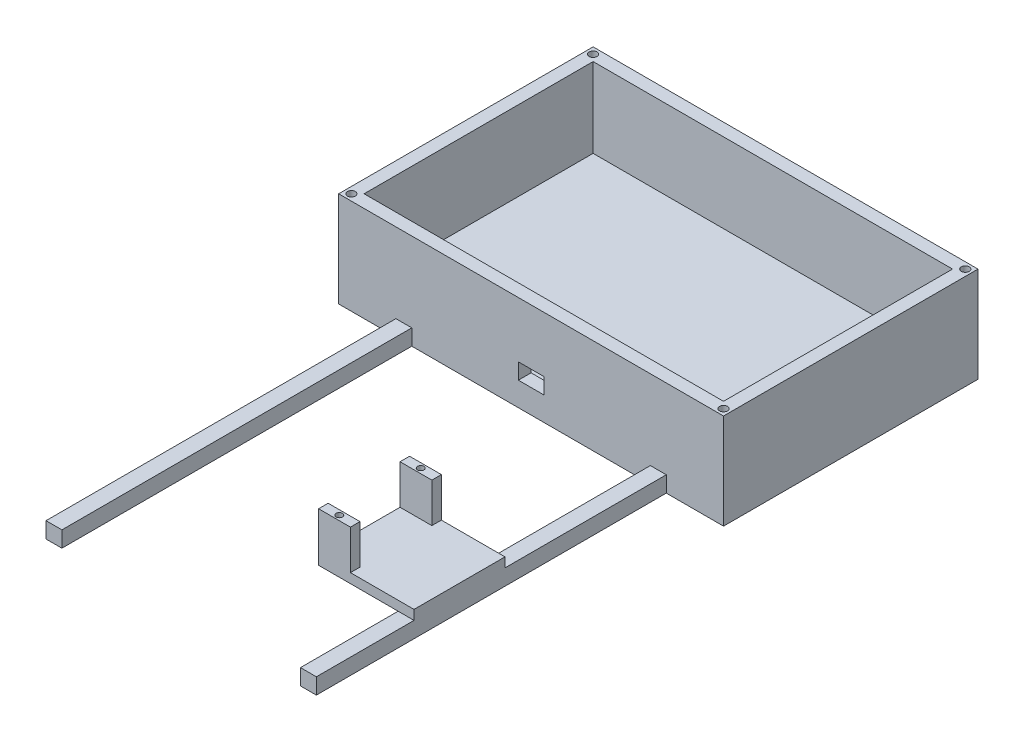
SolidWorks part; units mm, degrees
ref_plane "Front Plane" through (0, 0, 0) normal (0, 0, 1) x (1, 0, 0)
ref_plane "Top Plane" through (0, 0, 0) normal (0, 1, 0) x (1, 0, 0)
ref_plane "Right Plane" through (0, 0, 0) normal (1, 0, 0) x (0, 0, -1)
sketch "Sketch1" plane through (0, 0, 0) normal (0, 1, 0) x (1, 0, 0)
  line L5 (-55, 0) -> (55, 0) construction
  line L6 (-42.5, -81) -> (-42.5, 29)
  line L7 (-42.5, -81) -> (-37.5, -81)
  line L8 (0, -55) -> (0, 55) construction
  line L9 (42.5, -81) -> (37.5, -81)
  line L11 (-37.5, -81) -> (-37.5, 29)
  line L12 (37.5, -81) -> (37.5, 29)
  line L13 (37.5, 29) -> (-37.5, 29)
  line L14 (42.5, -81) -> (42.5, 29)
  line L15 (-42.5, 29) -> (-60.5, 29)
  line L16 (42.5, 29) -> (60.5, 29)
  line L17 (-60.5, 29) -> (-60.5, 109)
  line L18 (-60.5, 109) -> (60.5, 109)
  line L19 (60.5, 109) -> (60.5, 29)
  point P0 (0, 0)
  dimension "D1" = 110
  dimension "D2" = 18
  dimension "D3" = 29
  dimension "D4" = 5
  dimension "D5" = 110
  dimension "D6" = 80
  dimension "D7" = 75
  dimension "D8" = 18
extrude "Boss-Extrude1" add sketch "Sketch1" along normal blind 5
sketch "Sketch2" plane through (0, 5, 0) normal (0, 1, 0) x (1, 0, 0)
  line L0 (-37.5, 29) -> (-60.5, 29) construction
  line L2 (56.5, 33) -> (56.5, 105)
  line L3 (-60.5, 29) -> (60.5, 29)
  line L5 (-60.5, 109) -> (60.5, 109)
  line L7 (-56.5, 105) -> (56.5, 105)
  line L8 (-56.5, 33) -> (-56.5, 105)
  line L9 (-56.5, 33) -> (56.5, 33)
  line L10 (-60.5, 29) -> (-60.5, 109) construction
  line L11 (60.5, 29) -> (60.5, 109) construction
  line M10 (-37.5, 29) -> (37.5, 29)
  line M17 (-60.5, 29) -> (-42.5, 29)
  line M20 (42.5, 29) -> (60.5, 29)
  line M21 (60.5, 29) -> (60.5, 109)
  line M22 (60.5, 109) -> (-60.5, 109)
  line M23 (-60.5, 109) -> (-60.5, 29)
  dimension "D1" = 4
extrude "Boss-Extrude2" add sketch "Sketch2" along normal blind 25 contours L3 L9 L8 L7 L2 M17 M10 M20 M21 M22 M23
sketch "Sketch3" plane through (0, 30, 0) normal (0, 1, 0) x (1, 0, 0)
  line L0 (-60.5, 29) -> (-56.5, 33) construction
  line L1 (-56.5, 29) -> (-60.5, 33) construction
  line L2 (-42.5, 29) -> (-37.5, 29) construction
  line L4 (0, -55) -> (0, 55) construction
  line L5 (-39, 69) -> (39, 69) construction
  line L8 (-60.5, 109) -> (-60.5, 29) construction
  line L10 (-60.5, 29) -> (60.5, 29) construction
  circle A0 centre (-58.5, 31) radius 1.25
  circle A1 centre (58.5, 31) radius 1.25
  circle A2 centre (-58.5, 107) radius 1.25
  circle A3 centre (58.5, 107) radius 1.25
  dimension "D1" = 2.5
  dimension "D2" = 40
extrude "Cut-Extrude1" cut sketch "Sketch3" against normal blind 6
sketch "Sketch4" plane through (0, 5, 0) normal (0, 1, 0) x (1, 0, 0)
  line L0 (42.5, -50.3) -> (42.5, -21.7)
  line L2 (42.5, -81) -> (42.5, 29) construction
  line L3 (42.5, -21.7) -> (12.5, -21.7)
  line L4 (42.5, -50.3) -> (12.5, -50.3)
  line L5 (12.5, -21.7) -> (12.5, -50.3)
  line L6 (0, -55) -> (0, 55) construction
  line L7 (-60.5, 29) -> (60.5, 29) construction
  point P5 (42.5, -36)
  dimension "D1" = 65
  dimension "D2" = 28.6
  dimension "D3" = 12.5
extrude "Boss-Extrude3" add sketch "Sketch4" along normal blind 3
sketch "Sketch5" plane through (0, 8, 0) normal (0, 1, 0) x (1, 0, 0)
  line L1 (12.5, -21.7) -> (22.5, -21.7)
  line L2 (12.5, -21.7) -> (12.5, -24.7)
  line L3 (12.5, -24.7) -> (22.5, -24.7)
  line L4 (22.5, -21.7) -> (22.5, -24.7)
  line L5 (12.5, -50.3) -> (22.5, -50.3)
  line L6 (12.5, -50.3) -> (12.5, -47.3)
  line L7 (12.5, -47.3) -> (22.5, -47.3)
  line L8 (22.5, -50.3) -> (22.5, -47.3)
  dimension "D1" = 10
  dimension "D2" = 3
  dimension "D3" = 3
  dimension "D4" = 10
extrude "Boss-Extrude4" add sketch "Sketch5" along normal blind 12.4
sketch "Sketch6" plane through (0, 20.4, 0) normal (0, 1, 0) x (1, 0, 0)
  line L0 (12.5, -21.7) -> (22.5, -24.7) construction
  line L1 (12.5, -24.7) -> (22.5, -21.7) construction
  line L2 (12.5, -47.3) -> (22.5, -50.3) construction
  line L3 (12.5, -50.3) -> (22.5, -47.3) construction
  circle A0 centre (17.5, -48.8) radius 1
  circle A1 centre (17.5, -23.2) radius 1
  dimension "D1" = 2
  dimension "D2" = 2
extrude "Cut-Extrude2" cut sketch "Sketch6" against normal blind 4
sketch "Sketch12" plane through (0, 0, -29) normal (0, 0, 1) x (1, 0, 0)
  line L0 (0, -55) -> (0, 55) construction
  line L1 (-4, 7.5) -> (4, 7.5)
  line L2 (-4, 7.5) -> (-4, 12.5)
  line L3 (-4, 12.5) -> (4, 12.5)
  line L4 (4, 7.5) -> (4, 12.5)
  line L5 (-4, 7.5) -> (4, 12.5) construction
  line L6 (-4, 12.5) -> (4, 7.5) construction
  line L7 (55, 0) -> (-55, 0) construction
  point P0 (0, 10)
  dimension "D1" = 10
  dimension "D2" = 8
  dimension "D3" = 5
extrude "Cut-Extrude3" cut sketch "Sketch12" against normal blind 21
